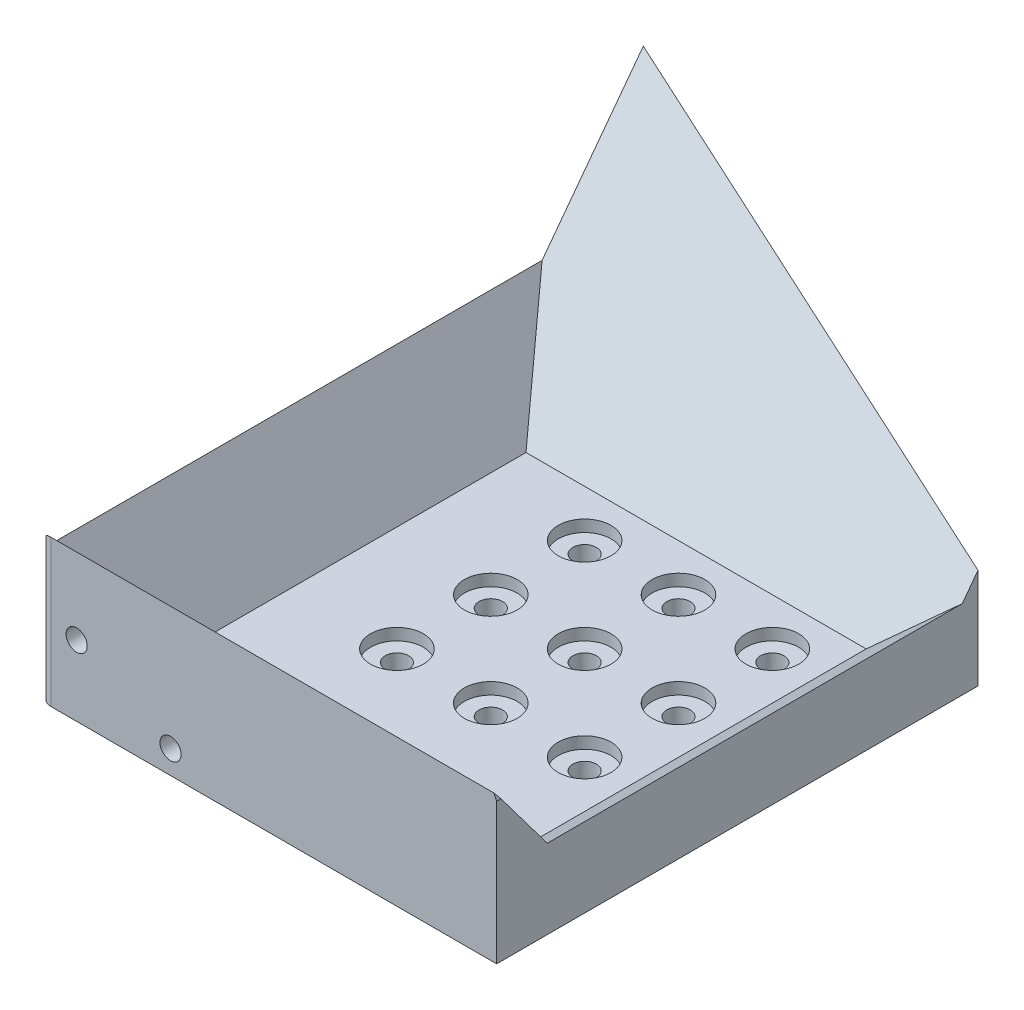
SolidWorks part; units mm, degrees
material "ABS"
ref_plane "前基準面" through (0, 0, 0) normal (0, 0, 1) x (1, 0, 0)
ref_plane "上基準面" through (0, 0, 0) normal (0, 1, 0) x (1, 0, 0)
ref_plane "右基準面" through (0, 0, 0) normal (1, 0, 0) x (0, 0, -1)
sketch "草圖1" plane through (0, 0, 0) normal (0, 1, 0) x (1, 0, 0)
  line L1 (0, 0) -> (62, 0)
  line L2 (0, 0) -> (0, 62)
  line L3 (0, 62) -> (62, 62)
  line L4 (62, 0) -> (62, 62)
  dimension "D1" = 62
  dimension "D2" = 62
extrude "填料-伸長1" add sketch "草圖1" along normal blind 19
sketch "草圖4" plane through (0, 19, 0) normal (0, 1, 0) x (1, 0, 0)
  line L5 (2, 60) -> (60, 60)
  line L6 (2, 60) -> (2, 2)
  line L7 (2, 2) -> (60, 2)
  line L8 (60, 60) -> (60, 2)
  dimension "D3" = 58
  dimension "D4" = 58
extrude "除料-伸長1" cut sketch "草圖4" against normal blind 17
sketch "草圖5" plane through (0, 19, 0) normal (0, 1, 0) x (1, 0, 0)
  line L1 (0, 0) -> (-8, 0)
  line L2 (0, 0) -> (0, 62)
  line L3 (0, 62) -> (-8, 62)
  line L4 (-8, 0) -> (-8, 62)
  dimension "D1" = 8
extrude "填料-伸長2" add sketch "草圖5" against normal blind 19
sketch "草圖7" plane through (0, 0, -60) normal (0, 0, 1) x (1, 0, 0)
  line L1 (60, 2) -> (2, 2)
  line L2 (60, 2) -> (60, 19)
  line L3 (60, 19) -> (2, 19)
  line L4 (2, 2) -> (2, 19)
extrude "除料-伸長2" cut sketch "草圖7" against normal blind 19
sketch "草圖8" plane through (0, 0, -62) normal (0, 0, -1) x (-1, 0, 0)
  line L0 (-2, 2) -> (8, 19)
  line L1 (8, 19) -> (-2, 19)
  line L2 (-2, 19) -> (-2, 2)
extrude "除料-伸長3" cut sketch "草圖8" against normal blind 108
sketch "草圖9" plane through (0, 0, -62) normal (0, 0, -1) x (-1, 0, 0)
  line L0 (8, 0) -> (8, 19) construction
  line L1 (-62, 0) -> (8, 0)
  line L2 (-62, 0) -> (-62, 2)
  line L3 (-62, 2) -> (8, 2)
  line L4 (8, 0) -> (8, 2)
extrude "填料-伸長3" add sketch "草圖9" along normal blind 28
sketch "草圖10" plane through (0, 2, 0) normal (0, 1, 0) x (1, 0, 0)
  line L1 (62, 90) -> (-8, 90)
  line L2 (62, 90) -> (62, 62)
  line L3 (62, 62) -> (-8, 62)
  line L4 (-8, 90) -> (-8, 62)
extrude "填料-伸長4" add sketch "草圖10" along normal blind 40
sketch "草圖11" plane through (-8, 0, 0) normal (-1, 0, 0) x (0, 0, 1)
  line L0 (-90, 42) -> (-62, 2)
  line L1 (-90, 42) -> (-62, 42)
  line L2 (-90, 0) -> (0, 0) construction
  line L3 (-62, 0) -> (-62, 2)
  line L4 (-62, 42) -> (-62, 2)
  dimension "D1" = 2
extrude "除料-伸長5" cut sketch "草圖11" against normal blind 90 contours L4 L0 L1
sketch "草圖14" plane through (0, 19, 0) normal (0, 1, 0) x (1, 0, 0)
  line L1 (2, 0) -> (62, 0)
  line L2 (2, 0) -> (2, 62)
  line L3 (2, 62) -> (62, 62)
  line L4 (62, 0) -> (62, 62)
extrude "除料-伸長6" cut sketch "草圖14" against normal blind 17
sketch "草圖15" plane through (62, 0, 0) normal (1, 0, 0) x (0, 0, -1)
  line L1 (62, 2) -> (0, 2)
  line L2 (62, 2) -> (62, 0)
  line L3 (62, 0) -> (0, 0)
  line L4 (0, 2) -> (0, 0)
extrude "填料-伸長6" add sketch "草圖15" along normal blind 8
sketch "草圖18" plane through (0, 2, 0) normal (0, 1, 0) x (1, 0, 0)
  line L0 (2, 0) -> (70, 0) construction
  line L1 (70, 62) -> (60, 62)
  line L2 (70, 62) -> (70, 0)
  line L3 (70, 0) -> (60, 0)
  line L4 (60, 62) -> (60, 0)
  dimension "D1" = 10
extrude "填料-伸長8" add sketch "草圖18" along normal blind 19
sketch "草圖19" plane through (0, 0, 0) normal (0, 0, 1) x (1, 0, 0)
  line L0 (60, 2) -> (70, 10.5)
  line L1 (70, 21) -> (70, 0) construction
  line L2 (70, 10.5) -> (70, 21)
  line L3 (70, 21) -> (60, 21)
  line L4 (60, 21) -> (60, 2)
extrude "除料-伸長7" cut sketch "草圖19" against normal blind 62
sketch "草圖20" plane through (62, 0, 0) normal (1, 0, 0) x (0, 0, -1)
  line L0 (90, 42) -> (62, 2)
  line L1 (62, 2) -> (62, 0)
  line L2 (62, 0) -> (90, 0)
  line L3 (90, 0) -> (90, 42)
extrude "填料-伸長9" add sketch "草圖20" along normal blind 8
sketch "草圖23" plane through (0, 0, 0) normal (0, 0, 1) x (1, 0, 0)
  line L0 (70, 10.5) -> (70, 0) construction
  line L1 (-8, 0) -> (70, 0)
  line L2 (-8, 0) -> (-8, 2)
  line L3 (-8, 2) -> (70, 2)
  line L4 (70, 0) -> (70, 2)
  dimension "D1" = 2
extrude "填料-伸長13" add sketch "草圖23" along normal blind 28
sketch "草圖25" plane through (0, 2, 0) normal (0, 1, 0) x (1, 0, 0)
  line L1 (70, 0) -> (-8, 0)
  line L2 (70, 0) -> (70, -28)
  line L3 (70, -28) -> (-8, -28)
  line L4 (-8, 0) -> (-8, -28)
extrude "填料-伸長14" add sketch "草圖25" along normal blind 40
sketch "草圖26" plane through (-8, 0, 0) normal (-1, 0, 0) x (0, 0, 1)
  line L0 (0, 0) -> (0, 2)
  line L4 (28, 42) -> (0, 42)
  line L5 (0, 42) -> (0, 2)
  line L6 (28, 42) -> (0, 2)
  dimension "D1" = 2
  dimension "D2" = 28
extrude "除料-伸長8" cut sketch "草圖26" against normal blind 99
sketch "草圖34" plane through (70, 0, 0) normal (1, 0, 0) x (0, 0, -1)
  line L0 (0, 2) -> (2, 2)
  line L1 (2, 2) -> (-28, 42)
  line L2 (-28, 42) -> (-28, 2)
  line L3 (-28, 0) -> (-28, 42) construction
  line L4 (-28, 2) -> (2, 2)
  line M2 (0, 2) -> (-28, 42)
  line M3 (-28, 42) -> (-28, 0)
  line M8 (0, 10.5) -> (0, 2)
  dimension "D1" = 2
extrude "填料-伸長19" add sketch "草圖34" against normal blind 78 contours L4 M3 M2 | L1 M8 M2 | L0 L1 M8
sketch "草圖36" plane through (-8, 0, 0) normal (-1, 0, 0) x (0, 0, 1)
  line L0 (-62, 2) -> (-60, 2)
  line L1 (-90, 42) -> (-60, 2)
  line L2 (-60, 2) -> (-90, 2)
  line L3 (-90, 0) -> (-90, 42) construction
  line L4 (-90, 2) -> (-90, 42)
  line M5 (-62, 19) -> (-62, 2)
  line M6 (-62, 2) -> (-90, 42)
  line M7 (-90, 42) -> (-90, 0)
  dimension "D1" = 2
extrude "填料-伸長20" add sketch "草圖36" against normal blind 78 contours L2 M6 M7 | L1 M6 M5 | L1 L0 M5
sketch "草圖37" plane through (0, 0, -62) normal (0, 0, -1) x (-1, 0, 0)
  line L0 (8, 4.6667) -> (-0.4314, 4.6667)
  line L1 (-0.4314, 4.6667) -> (8, 19)
  line L2 (8, 19) -> (8, 4.6667)
extrude "填料-伸長21" add sketch "草圖37" along normal blind 24
sketch "草圖38" plane through (0, 0, -62) normal (0, 0, -1) x (-1, 0, 0)
  line L0 (-63.1373, 4.6667) -> (-70, 4.6667)
  line L1 (-70, 4.6667) -> (-70, 10.5)
  line L2 (-70, 10.5) -> (-63.1373, 4.6667)
extrude "填料-伸長22" add sketch "草圖38" along normal blind 24
sketch "草圖39" plane through (0, 0, 0) normal (0, 0, 1) x (1, 0, 0)
  line L0 (-8, 19) -> (-8, 4.6667)
  line L1 (-8, 4.6667) -> (0.4314, 4.6667)
  line L2 (0.4314, 4.6667) -> (-8, 19)
extrude "填料-伸長23" add sketch "草圖39" along normal blind 24
sketch "草圖40" plane through (0, 0, 0) normal (0, 0, 1) x (1, 0, 0)
  line L0 (70, 10.5) -> (63.1373, 4.6667)
  line L1 (63.1373, 4.6667) -> (70, 4.6667)
  line L2 (70, 4.6667) -> (70, 10.5)
extrude "填料-伸長24" add sketch "草圖40" along normal blind 24
sketch "草圖43" plane through (0, 0, 0) normal (0, -1, 0) x (-1, 0, 0)
  line L1 (8, -28) -> (-70, -28)
  line L2 (8, -28) -> (8, 90)
  line L3 (8, 90) -> (-70, 90)
  line L4 (-70, -28) -> (-70, 90)
extrude "填料-伸長25" add sketch "草圖43" along normal blind 1
sketch "草圖46" plane through (0, 0, -90) normal (0, 0, -1) x (-1, 0, 0)
  line L0 (-70, 42) -> (-60, 42)
  line L1 (-70, 42) -> (8, 42) construction
  line L2 (-70, 42) -> (-70, 21)
  line L3 (-70, -1) -> (-70, 42) construction
  line L4 (-70, 21) -> (-60, 42)
  dimension "D1" = 10
  dimension "D2" = 21
extrude "除料-伸長14" cut sketch "草圖46" against normal blind 127
sketch "草圖47" plane through (0, 0, 28) normal (0, 0, 1) x (1, 0, 0)
  line L0 (-8, 42) -> (2, 42)
  line L1 (-8, 42) -> (60, 42) construction
  line L2 (-8, 42) -> (-8, 21)
  line L3 (-8, 42) -> (-8, -1) construction
  line L4 (-8, 21) -> (2, 42)
  dimension "D1" = 10
  dimension "D2" = 21
extrude "除料-伸長15" cut sketch "草圖47" against normal blind 80
sketch "草圖49" plane through (0, 2, 0) normal (0, 1, 0) x (1, 0, 0)
  circle A0 centre (52, 52) radius 2
  circle A1 centre (36, 52) radius 2
  circle A2 centre (20, 52) radius 2
  circle A3 centre (36, 36) radius 2
  circle A4 centre (20, 36) radius 2
  circle A5 centre (36, 20) radius 2
  circle A6 centre (20, 20) radius 2
  circle A7 centre (52, 36) radius 2
  circle A8 centre (52, 20) radius 2
  dimension "D3" = 4
  dimension "D1" = 3
  dimension "D2" = 3
extrude "除料-伸長17" cut sketch "草圖49" against normal blind 19
sketch "草圖50" plane through (0, 2, 0) normal (0, 1, 0) x (1, 0, 0)
  circle A0 centre (52, 20) radius 4.5
  circle A1 centre (36, 20) radius 4.5
  circle A2 centre (20, 20) radius 4.5
  circle A3 centre (36, 36) radius 4.5
  circle A4 centre (20, 36) radius 4.5
  circle A5 centre (36, 52) radius 4.5
  circle A6 centre (20, 52) radius 4.5
  circle A7 centre (52, 36) radius 4.5
  circle A8 centre (52, 52) radius 4.5
  dimension "D1" = 9
  dimension "D2" = 3
  dimension "D3" = 3
extrude "除料-伸長18" cut sketch "草圖50" against normal blind 2
sketch "草圖55" plane through (0, 0, -90) normal (0, 0, -1) x (-1, 0, 0)
  circle A1 centre (-5, 7) radius 2
  circle A2 centre (-13, 7) radius 2
  circle A3 centre (-5, 15) radius 2
  circle A4 centre (-13, 15) radius 2
  circle A5 centre (-5, 23) radius 2
  circle A6 centre (-13, 23) radius 2
  circle A7 centre (3, 15) radius 2
  circle A8 centre (3, 23) radius 2
extrude "除料-伸長20" cut sketch "草圖55" against normal blind 7.5
sketch "草圖57" plane through (0, 0, -90) normal (0, 0, -1) x (-1, 0, 0)
  line L2 (8, -1) -> (-70, -1) construction
  line L3 (-28.0955, 31.1638) -> (8, 31.1638)
  line L4 (-28.0955, 31.1638) -> (-28.0955, -1)
  line L5 (-28.0955, -1) -> (8, -1)
  line L6 (8, 31.1638) -> (8, -1)
extrude "填料-伸長26" add sketch "草圖57" against normal blind 7
sketch "草圖63" plane through (0, 0, -90) normal (0, 0, -1) x (-1, 0, 0)
  circle A0 centre (-64, 7) radius 1.8
  circle A1 centre (-56, 7) radius 1.8
  circle A2 centre (-48, 7) radius 1.8
  circle A3 centre (-56, 15) radius 1.8
  circle A4 centre (-48, 15) radius 1.8
  circle A5 centre (-56, 23) radius 1.8
  circle A6 centre (-48, 23) radius 1.8
  circle A7 centre (-64, 15) radius 1.8
  circle A8 centre (-64, 23) radius 1.8
  dimension "D3" = 3.6
  dimension "D4" = 3
  dimension "D5" = 3
extrude "除料-伸長23" cut sketch "草圖63" against normal blind 7.5
sketch "草圖64" plane through (0, -1, 0) normal (0, -1, 0) x (-1, 0, 0)
  line L0 (-70, 90) -> (-70, -28) construction
  line L1 (8, -28) -> (-70, -28)
  line L2 (8, -28) -> (8, 90)
  line L3 (8, 90) -> (-70, 90)
  line L4 (-70, -28) -> (-70, 90)
  line L5 (8, 90) -> (-70, 90) construction
extrude "填料-伸長27" add sketch "草圖64" along normal blind 1
sketch "草圖65" plane through (0, -1, 0) normal (0, 1, 0) x (1, 0, 0)
  circle A0 centre (52, 52) radius 2
  circle A1 centre (36, 52) radius 2
  circle A2 centre (20, 52) radius 2
  circle A3 centre (36, 36) radius 2
  circle A4 centre (20, 36) radius 2
  circle A5 centre (36, 20) radius 2
  circle A6 centre (20, 20) radius 2
  circle A7 centre (52, 36) radius 2
  circle A8 centre (52, 20) radius 2
  dimension "D1" = 3
  dimension "D2" = 3
extrude "除料-伸長24" cut sketch "草圖65" against normal blind 29
sketch "草圖66" plane through (0, -2, 0) normal (0, -1, 0) x (-1, 0, 0)
  line L1 (8, 90) -> (-70, 90)
  line L2 (8, 90) -> (8, -28)
  line L3 (8, -28) -> (-70, -28)
  line L4 (-70, 90) -> (-70, -28)
extrude "填料-伸長28" add sketch "草圖66" along normal blind 1
sketch "草圖68" plane through (0, -2, 0) normal (0, 1, 0) x (1, 0, 0)
  circle A0 centre (20, 20) radius 2
  circle A1 centre (36, 20) radius 2
  circle A2 centre (52, 20) radius 2
  circle A3 centre (36, 36) radius 2
  circle A4 centre (52, 36) radius 2
  circle A5 centre (36, 52) radius 2
  circle A6 centre (52, 52) radius 2
  circle A7 centre (20, 36) radius 2
  circle A8 centre (20, 52) radius 2
  dimension "D1" = 3
  dimension "D2" = 3
extrude "除料-伸長25" cut sketch "草圖68" against normal blind 28
sketch "草圖69" plane through (0, 0, 28) normal (0, 0, 1) x (1, 0, 0)
  line L0 (-8, -3) -> (70, -3)
  line L1 (-8, -3) -> (-8, 49.0365)
  line L2 (70, -3) -> (70, 49.0365)
  line L3 (-8, 49.0365) -> (70, 49.0365)
extrude "除料-伸長26" cut sketch "草圖69" against normal blind 15
fillet "圓角1" radius 2 1 edges at (-8, 9, 13)
sketch "草圖71" plane through (0, -3, 0) normal (0, -1, 0) x (1, 0, 0)
  line L0 (-8, -90) -> (70, -69.0619)
  line L1 (70, -90) -> (70, 13) construction
  line L2 (70, -69.0619) -> (70, -90)
  line L3 (70, -90) -> (-8, -90)
  line L4 (77.1316, -25.2234) -> (124.2341, -12.5793) construction
extrude "除料-伸長27" cut sketch "草圖71" against normal through all
sketch "草圖73" plane through (-8, 0, 0) normal (-1, 0, 0) x (0, 0, 1)
  circle A0 centre (-9.4, 1) radius 1.8
  circle A2 centre (-1.4, 1) radius 1.8
  dimension "D1" = 3.6
  dimension "D2" = 3.6
extrude "除料-伸長28" cut sketch "草圖73" against normal blind 8
sketch "草圖74" plane through (0, 0, 13) normal (0, 0, 1) x (1, 0, 0)
  circle A0 centre (-1.6, 9) radius 1.8
  circle A1 centre (14.4, 1) radius 1.8
  dimension "D1" = 3.6
  dimension "D2" = 3.6
extrude "除料-伸長29" cut sketch "草圖74" against normal blind 8
